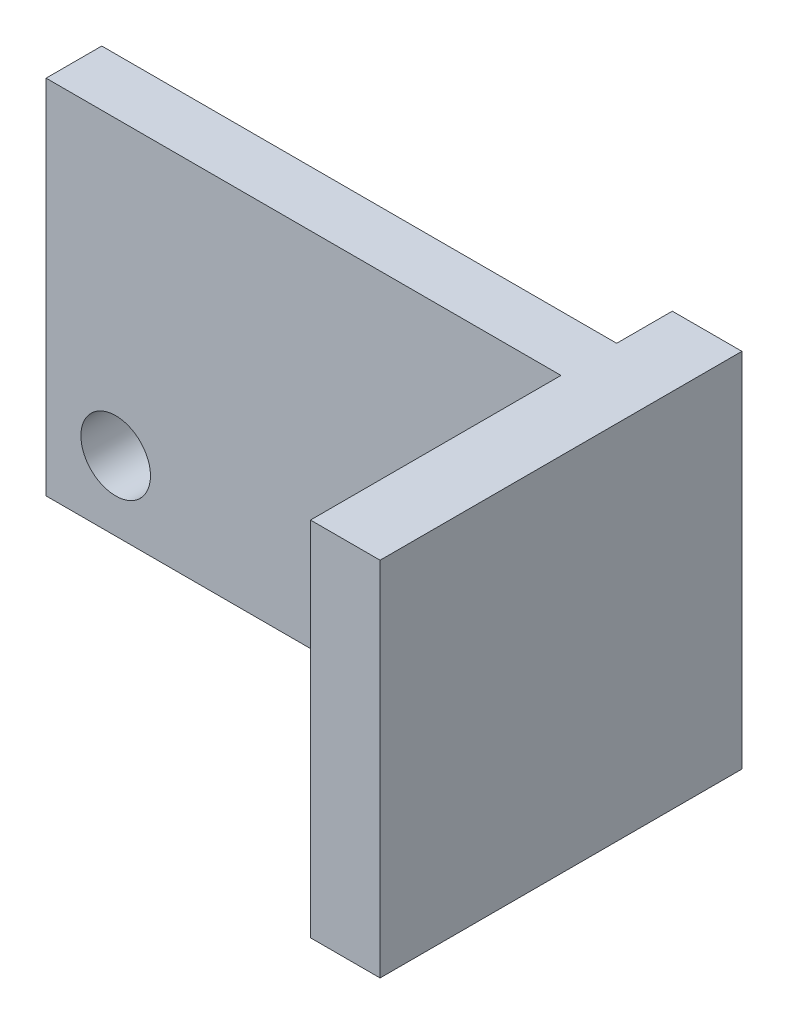
SolidWorks part; units mm, degrees
ref_plane "Plan de face" through (0, 0, 0) normal (0, 0, 1) x (1, 0, 0)
ref_plane "Plan de dessus" through (0, 0, 0) normal (0, 1, 0) x (1, 0, 0)
ref_plane "Plan de droite" through (0, 0, 0) normal (1, 0, 0) x (0, 0, -1)
sketch "Esquisse1" plane through (0, 0, 0) normal (0, 0, 1) x (1, 0, 0)
  line L1 (0, 0) -> (21, 0)
  line L2 (0, 0) -> (0, 13)
  line L3 (0, 13) -> (21, 13)
  line L4 (21, 0) -> (21, 13)
  dimension "D1" = 13
  dimension "D2" = 21
extrude "Boss.-Extru.1" add sketch "Esquisse1" along normal blind 2
sketch "Esquisse2" plane through (0, 0, 2) normal (0, 0, 1) x (1, 0, 0)
  line L0 (0, 13) -> (0, 0) construction
  line L1 (0, 0) -> (21, 0) construction
  circle A0 centre (2.5, 2.5) radius 1.25
  dimension "D1" = 2.5
  dimension "D2" = 2.5
  dimension "D3" = 2.5
extrude "Enlèv. mat.-Extru.1" cut sketch "Esquisse2" against normal blind 2
sketch "Esquisse3" plane through (0, 0, 2) normal (0, 0, 1) x (1, 0, 0)
  line L0 (21, 13) -> (0, 13) construction
  line L1 (18.5, 13) -> (21, 13)
  line L2 (18.5, 13) -> (18.5, 0)
  line L3 (18.5, 0) -> (21, 0)
  line L4 (21, 13) -> (21, 0)
  dimension "D1" = 2.5
extrude "Boss.-Extru.2" add sketch "Esquisse3" along normal blind 9 and the other way blind 4
